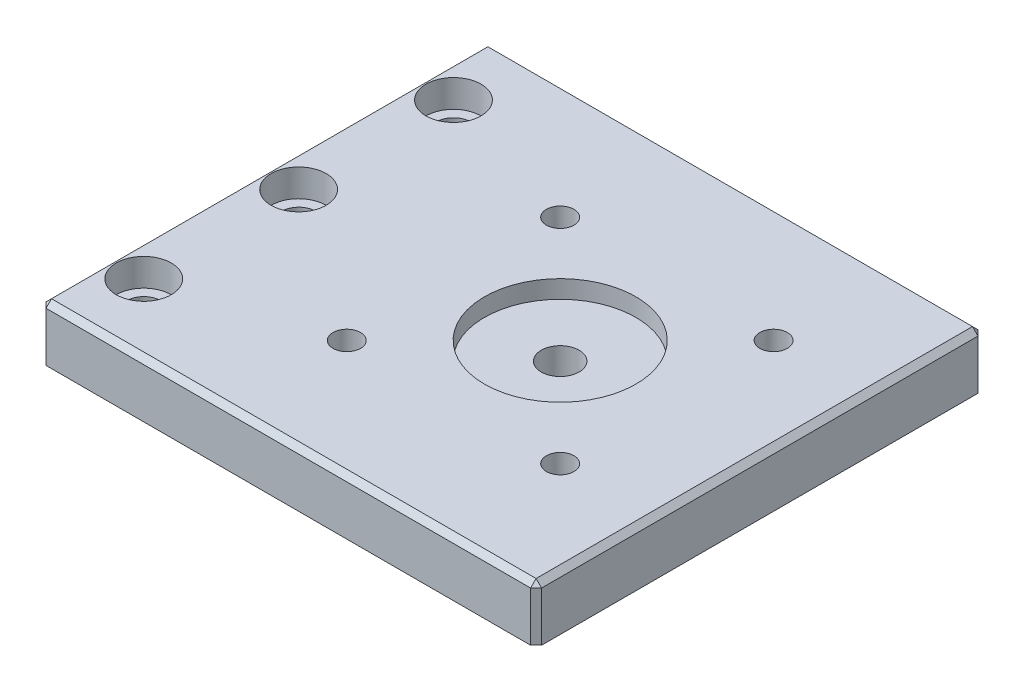
SolidWorks part; units mm, degrees
material "6061 合金"
ref_plane "前视基准面" through (0, 0, 0) normal (0, 0, 1) x (1, 0, 0)
ref_plane "上视基准面" through (0, 0, 0) normal (0, 1, 0) x (1, 0, 0)
ref_plane "右视基准面" through (0, 0, 0) normal (1, 0, 0) x (0, 0, -1)
other "Configuration Table"
sketch "草图1" plane through (0, 0, 0) normal (0, 1, 0) x (1, 0, 0)
  line L1 (-36, 32.5) -> (36, 32.5)
  line L2 (-36, 32.5) -> (-36, -32.5)
  line L3 (-36, -32.5) -> (36, -32.5)
  line L4 (36, 32.5) -> (36, -32.5)
  line L5 (-36, 32.5) -> (36, -32.5) construction
  line L6 (-36, -32.5) -> (36, 32.5) construction
  point P0 (0, 0)
  dimension "D1" = 65
  dimension "D2" = 72
extrude "凸台-拉伸1" add sketch "草图1" along normal mid plane 8
sketch "草图4" plane through (0, 4, 0) normal (0, 1, 0) x (1, 0, 0)
  line L2 (-36, 32.5) -> (-36, -32.5) construction
  line L3 (36, 32.5) -> (-36, 32.5) construction
  point P0 (7, 0)
  dimension "D1" = 43
  dimension "D2" = 32.5
hole_wizard "孔1" positions "草图4" profile "草图3" legacy
sketch "草图3" plane through (7, 4, 0) normal (1, 0, 0) x (0, 0, 1)
  line L0 (0, 0) -> (0, 100)
  line L1 (0, 100) -> (2.75, 100)
  line L2 (2.75, 100) -> (2.75, 2.6)
  line L3 (2.75, 2.6) -> (11, 2.6)
  line L4 (11, 2.6) -> (11, 0)
  line L5 (11, 0) -> (0, 0)
  line L6 (0, 110) -> (0, -10) construction
  dimension "直径" = 5.5
  dimension "深度" = 100
  dimension "柱坑直径" = 22
  dimension "柱坑深度" = 2.6
sketch "草图5" plane through (0, -4, 0) normal (0, -1, 0) x (1, 0, 0)
  line L1 (-8.5, 15.5) -> (22.5, 15.5) construction
  line L2 (-8.5, 15.5) -> (-8.5, -15.5) construction
  line L3 (-8.5, -15.5) -> (22.5, -15.5) construction
  line L4 (22.5, 15.5) -> (22.5, -15.5) construction
  line L5 (-8.5, 15.5) -> (22.5, -15.5) construction
  line L6 (-8.5, -15.5) -> (22.5, 15.5) construction
  point P0 (7, 0)
  dimension "D1" = 31
  dimension "D2" = 31
sketch "草图8" plane through (0, -4, 0) normal (0, -1, 0) x (-1, 0, 0)
  point P0 (-22.5, 15.5)
  point P3 (8.5, 15.5)
  point P6 (8.5, -15.5)
  point P9 (-22.5, -15.5)
hole_wizard "孔2" positions "草图8" profile "草图7" legacy
sketch "草图7" plane through (22.5, -4, -15.5) normal (1, 0, 0) x (0, 0, -1)
  line L0 (0, 0) -> (0, 100)
  line L1 (0, 100) -> (2, 100)
  line L2 (2, 100) -> (2, 3)
  line L3 (2, 3) -> (3, 3)
  line L4 (3, 3) -> (3, 0)
  line L5 (3, 0) -> (0, 0)
  line L6 (0, 110) -> (0, -10) construction
  dimension "直径" = 4
  dimension "深度" = 100
  dimension "柱坑直径" = 6
  dimension "柱坑深度" = 3
sketch "草图11" plane through (0, 4, 0) normal (0, 1, 0) x (1, 0, 0)
  line L0 (-38.9643, 0) -> (0, 0) construction
  line L2 (-36, 32.5) -> (-36, -32.5) construction
  line L3 (-31, 35.1015) -> (-31, -35.2695) construction
  point P0 (-31, 22.5)
  point P2 (-31, 0)
  point P4 (-31, -22.5)
  dimension "D1" = 5
  dimension "D2" = 45
hole_wizard "孔3" positions "草图11" profile "草图10" legacy
sketch "草图10" plane through (-31, 4, -22.5) normal (1, 0, 0) x (0, 0, 1)
  line L0 (0, 0) -> (0, 100)
  line L1 (0, 100) -> (2.5, 100)
  line L2 (2.5, 100) -> (2.5, 4)
  line L3 (2.5, 4) -> (4, 4)
  line L4 (4, 4) -> (4, 0)
  line L5 (4, 0) -> (0, 0)
  line L6 (0, 110) -> (0, -10) construction
  dimension "直径" = 5
  dimension "深度" = 100
  dimension "柱坑直径" = 8
  dimension "柱坑深度" = 4
chamfer "倒角1" distance 0.8 angle 45 8 edges at (-36, 0, -32.5) (36, 0, -32.5) (36, 0, 32.5) (-36, 0, 32.5) (-36, 4, 0) (0, 4, -32.5) (36, 4, 0) (0, 4, 32.5)
